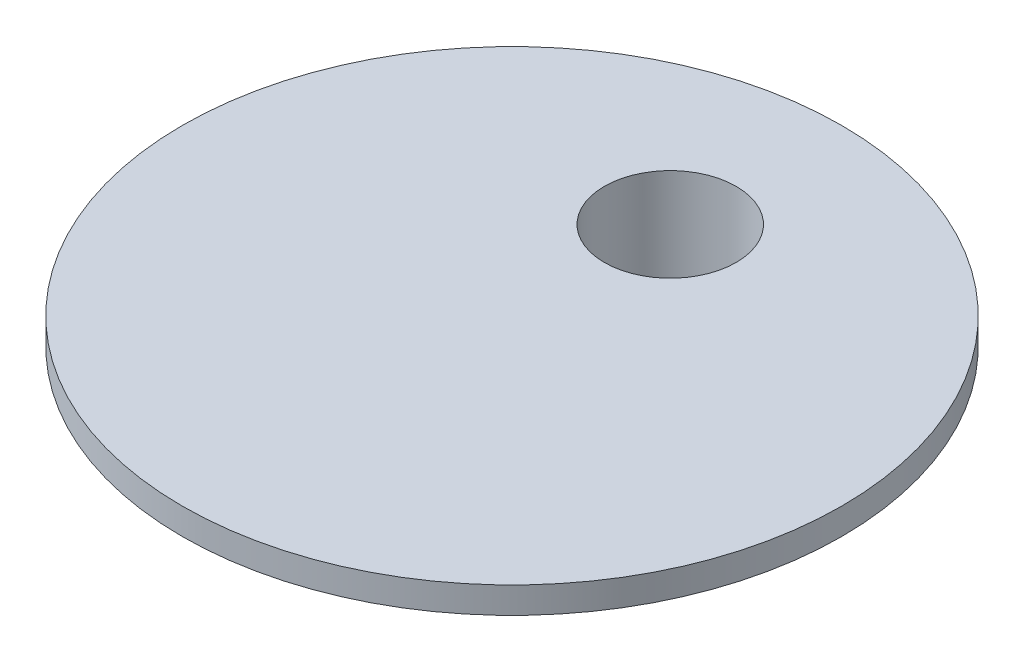
SolidWorks part; units mm, degrees
ref_plane "Front" through (0, 0, 0) normal (0, 0, 1) x (1, 0, 0)
ref_plane "Top" through (0, 0, 0) normal (0, 1, 0) x (1, 0, 0)
ref_plane "Right" through (0, 0, 0) normal (1, 0, 0) x (0, 0, -1)
sketch "Sketch1" plane through (0, 0, 0) normal (0, 1, 0) x (1, 0, 0)
  line L0 (0, 0) -> (0, 125) construction
  circle A0 centre (0, 0) radius 125
  circle A1 centre (0, 60) radius 25
  dimension "D1" = 250
  dimension "D3" = 50
  dimension "D4" = 60
extrude "Boss-Extrude1" add sketch "Sketch1" along normal blind 10
sketch "Sketch2" plane through (0, 0, 0) normal (0, -1, 0) x (1, 0, 0)
  circle A0 centre (0, -60) radius 25
  circle A1 centre (0, -60) radius 30
  dimension "D2" = 60
  dimension "D1" = 5
extrude "Boss-Extrude2" add sketch "Sketch2" along normal blind 85
